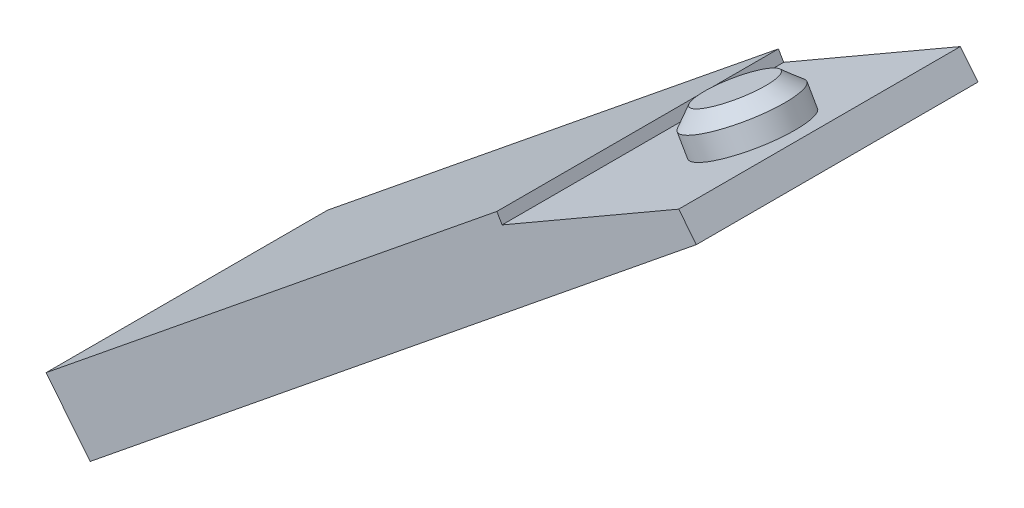
SolidWorks part; units mm, degrees
ref_plane "前视基准面" through (0, 0, 0) normal (0, 0, 1) x (1, 0, 0)
ref_plane "上视基准面" through (0, 0, 0) normal (0, 1, 0) x (1, 0, 0)
ref_plane "右视基准面" through (0, 0, 0) normal (1, 0, 0) x (0, 0, -1)
sketch "草图1" plane through (0, 0, 0) normal (0, 0, 1) x (1, 0, 0)
  line L0 (-38.8109, -2.7776) -> (-8.5, 14.7224)
  line L1 (0, 0) -> (8.1193, 22.3076) construction
  line L2 (0, 0) -> (0, 20.26) construction
  line L3 (-39.8109, -1.0455) -> (-9.5, 16.4545)
  line L4 (-39.8109, -1.0455) -> (-38.8109, -2.7776)
  line L5 (6.4984, 17.8542) -> (5.8143, 15.9748)
  arc A0 (5.8143, 15.9748) -> (-8.5, 14.7224) centre (0, 0) ccw
  arc A1 (6.4984, 17.8542) -> (-9.5, 16.4545) centre (0, 0) ccw
  dimension "D1" = 34
  dimension "D2" = 35
  dimension "D3" = 20
  dimension "D4" = 2
  dimension "D5" = 60
extrude "凸台-拉伸1" add sketch "草图1" along normal mid plane 18
sketch "草图2" plane through (-9.5, 16.4545, 0) normal (-0.5, 0.866, 0) x (0.866, 0.5, 0)
  line L0 (-35, 0) -> (-17.822, 0) construction
  line L1 (-35, -9) -> (-35, 9) construction
  circle A0 centre (-26, 0) radius 3.5
  dimension "D1" = 7
  dimension "D2" = 9
extrude "切除-拉伸1" cut sketch "草图2" against normal blind 18
sketch "草图3" plane through (0, 0, 0) normal (0, 0, 1) x (1, 0, 0)
  line L0 (-26.2668, 4.4648) -> (-69.3181, -30.3975)
  line L1 (-38.8109, -2.7776) -> (-8.5, 14.7224) construction
  line L2 (-69.3181, -30.3975) -> (-71.206, -28.066)
  line L3 (-71.206, -28.066) -> (-42.8748, -5.1239)
  line L4 (-26.2668, 4.4648) -> (-42.8748, -5.1239)
  line L5 (0, 0) -> (0, -50000) construction
  dimension "D1" = 9
  dimension "D2" = 3
  dimension "D3" = 20
  dimension "D4" = 73
extrude "凸台-拉伸2" add sketch "草图3" along normal mid plane 20 separate body
sketch "草图4" plane through (-8.5, 14.7224, 0) normal (-0.5, 0.866, 0) x (0.866, 0.5, 0)
  circle A2 centre (-26, 0) radius 3.5
  circle A3 centre (-26, 0) radius 3.5
  dimension "D1" = 0
extrude "凸台-拉伸3" add sketch "草图4" along normal blind 2.5
chamfer "倒角1" distance 1 angle 45 1 edges at (-35.2977, 2.1375, 0)
sketch "草图6" plane through (0, 0, 0) normal (0, 0, 1) x (1, 0, 0)
  line L0 (-38.8109, -2.7776) -> (-39.1825, -2.1339)
  line L2 (-38.8109, -2.7776) -> (-42.8748, -5.1239)
  line L3 (-42.8748, -5.1239) -> (-39.1825, -2.1339)
  line L5 (-26.2668, 4.4648) -> (-42.8748, -5.1239) construction
  line L6 (-42.8748, -5.1239) -> (-71.206, -28.066) construction
extrude "凸台-拉伸4" add sketch "草图6" along normal mid plane 20
sketch "草图7" plane through (0, 0, 0) normal (0, 0, 1) x (1, 0, 0)
  line L1 (-55.4129, -25.8234) -> (7.6337, -25.8234)
  line L2 (-55.4129, -25.8234) -> (-55.4129, 55.6228)
  line L3 (-55.4129, 55.6228) -> (7.6337, 55.6228)
  line L4 (7.6337, -25.8234) -> (7.6337, 55.6228)
extrude "切除-拉伸2" cut sketch "草图7" against normal mid plane 20
sketch "草图8" plane through (-12.5864, 15.5429, 0) normal (0.6293, -0.7771, 0) x (0.7771, 0.6293, 0)
  line L8 (-73, -10) -> (-17.6033, -10)
  line L9 (-17.6033, -10) -> (-17.6033, 10)
  line L10 (-17.6033, 10) -> (-73, 10)
  line L11 (-73, 10) -> (-73, -10)
  line L12 (-73, -10) -> (-17.6033, -10)
  line L13 (-17.6033, -10) -> (-17.6033, 10)
  line L14 (-17.6033, 10) -> (-73, 10)
  line L15 (-73, 10) -> (-73, -10)
  dimension "D1" = 0
extrude "凸台-拉伸5" add sketch "草图8" along normal blind 2
